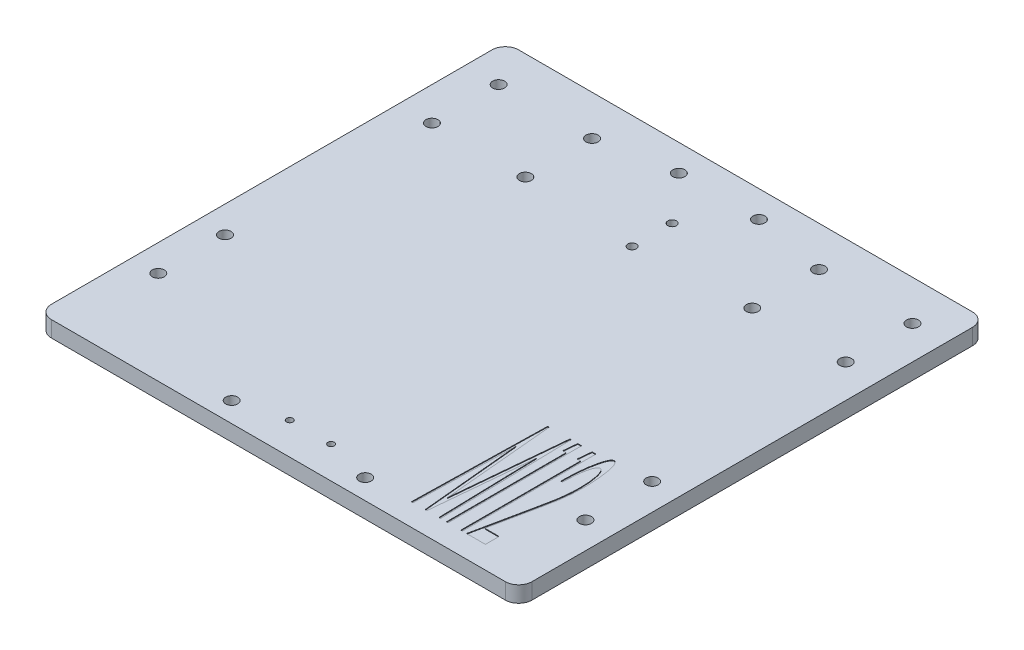
SolidWorks part; units mm, degrees
ref_plane "Front Plane" through (0, 0, 0) normal (0, 0, 1) x (1, 0, 0)
ref_plane "Top Plane" through (0, 0, 0) normal (0, 1, 0) x (1, 0, 0)
ref_plane "Right Plane" through (0, 0, 0) normal (1, 0, 0) x (0, 0, -1)
sketch "Sketch1" plane through (0, 0, 0) normal (0, 1, 0) x (1, 0, 0)
  line L1 (90, -87.5) -> (-90, -87.5)
  line L2 (90, -87.5) -> (90, 87.5)
  line L3 (90, 87.5) -> (-90, 87.5)
  line L4 (-90, -87.5) -> (-90, 87.5)
  line L5 (90, -87.5) -> (-90, 87.5) construction
  line L6 (90, 87.5) -> (-90, -87.5) construction
  point P0 (0, 0)
  dimension "D1" = 180
  dimension "D2" = 175
extrude "plate" add sketch "Sketch1" along normal blind 6
fillet "Fillet corners" radius 5 4 edges at (-90, 3, 87.5) (90, 3, 87.5) (90, 3, -87.5) (-90, 3, -87.5)
sketch "Sketch2" plane through (0, 6, 0) normal (0, 1, 0) x (1, 0, 0)
  line L0 (-90, 82.5) -> (-90, -82.5) construction
  line L1 (-77.5, 47.5) -> (-42.5, 47.5) construction
  line L2 (-77.5, 47.5) -> (-77.5, 72.5) construction
  line L3 (-77.5, 72.5) -> (-42.5, 72.5) construction
  line L4 (-42.5, 47.5) -> (-42.5, 72.5) construction
  line L5 (-77.5, 47.5) -> (-42.5, 72.5) construction
  line L6 (-77.5, 72.5) -> (-42.5, 47.5) construction
  line L7 (85, 87.5) -> (-85, 87.5) construction
  circle A0 centre (-77.5, 72.5) radius 2.25
  circle A1 centre (-42.5, 72.5) radius 2.25
  circle A2 centre (-42.5, 47.5) radius 2.25
  circle A3 centre (-77.5, 47.5) radius 2.25
  point P0 (-60, 60)
  dimension "D1" = 4.5
  dimension "D2" = 35
  dimension "D3" = 25
  dimension "D4" = 30
  dimension "D5" = 27.5
extrude "motor bracket holes" cut sketch "Sketch2" against normal through all
sketch "Sketch3" plane through (0, 6, 0) normal (0, 1, 0) x (1, 0, 0)
  line L0 (-7.75, -75.5) -> (7.75, -75.5) construction
  line L1 (0, 0) -> (0, -75.5) construction
  line L2 (-85, -87.5) -> (85, -87.5) construction
  circle A0 centre (-7.75, -75.5) radius 1.2
  circle A1 centre (7.75, -75.5) radius 1.2
  dimension "D1" = 2.4
  dimension "D2" = 12
  dimension "D3" = 15.5
extrude "caster holes" cut sketch "Sketch3" against normal through all
sketch "Sketch4" plane through (0, 6, 0) normal (0, 1, 0) x (1, 0, 0)
  line L0 (-85, -87.5) -> (85, -87.5) construction
  line L1 (-90, 82.5) -> (-90, -82.5) construction
  circle A0 centre (-80, -52.5) radius 2.25
  circle A1 centre (-80, -27.5) radius 2.25
  dimension "D3" = 4.5
  dimension "D1" = 25
  dimension "D2" = 35
  dimension "D4" = 10
extrude "ultrasound holes" cut sketch "Sketch4" against normal through all
sketch "Sketch6" plane through (0, 6, 0) normal (0, 1, 0) x (1, 0, 0)
  line L0 (-85, -87.5) -> (85, -87.5) construction
  circle A1 centre (-25, -80) radius 2.25
  dimension "D3" = 4.5
  dimension "D1" = 25
  dimension "D2" = 7.5
extrude "battery cage holes" cut sketch "Sketch6" against normal through all
sketch "Sketch5" plane through (0, 6, 0) normal (0, 1, 0) x (1, 0, 0)
  line L0 (85, 87.5) -> (-85, 87.5) construction
  line L1 (-15, 77.5) -> (15, 77.5) construction
  circle A0 centre (-15, 77.5) radius 2.25
  circle A1 centre (15, 77.5) radius 2.25
  point P4 (0, 77.5)
  dimension "D2" = 4.5
  dimension "D1" = 30
  dimension "D3" = 10
extrude "front holes" cut sketch "Sketch5" against normal through all
mirror "Mirror holes" about plane through (0, 0, 0) normal (1, 0, 0) of "battery cage holes", "motor bracket holes", "ultrasound holes"
sketch "Sketch7" plane through (0, 6, 0) normal (0, 1, 0) x (1, 0, 0)
  text T0 "M112" font "Century Gothic" height 50
extrude "team name" cut sketch "Sketch7" against normal blind 0.25
sketch "Sketch8" plane through (0, 6, 0) normal (0, 1, 0) x (1, 0, 0)
  line L0 (-43.7333, 60) -> (21.1634, 60) construction
  line L1 (-42.5, 72.5) -> (-42.5, 47.5) construction
  circle A0 centre (0, 45) radius 1.6
  circle A2 centre (0, 60) radius 1.6
  point P5 (-42.5, 60)
  point P12 (0, 0)
  dimension "D1" = 3.2
  dimension "D2" = 15
extrude "beacon holes" cut sketch "Sketch8" against normal through all
